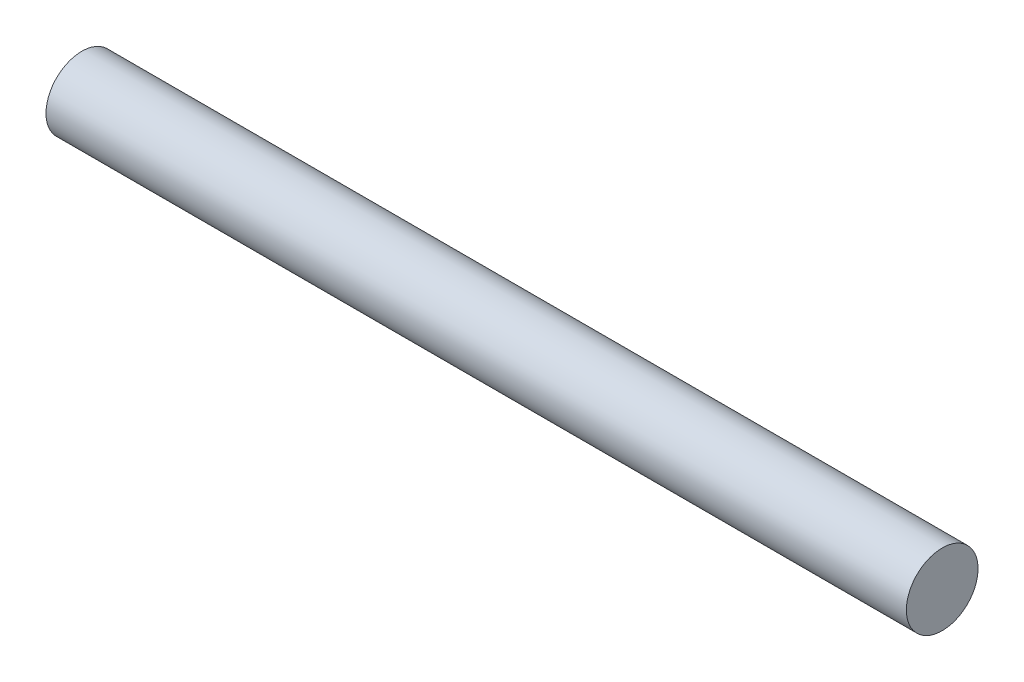
SolidWorks part; units mm, degrees
ref_plane "Front" through (0, 0, 0) normal (0, 0, 1) x (1, 0, 0)
ref_plane "Top" through (0, 0, 0) normal (0, 1, 0) x (1, 0, 0)
ref_plane "Right" through (0, 0, 0) normal (1, 0, 0) x (0, 0, -1)
sketch "草图1" plane through (0, 0, 0) normal (1, 0, 0) x (0, 0, -1)
  circle A0 centre (0, 0) radius 6.35
  dimension "D1" = 12.7
extrude "凸台-拉伸1" add sketch "草图1" along normal blind 152.4
